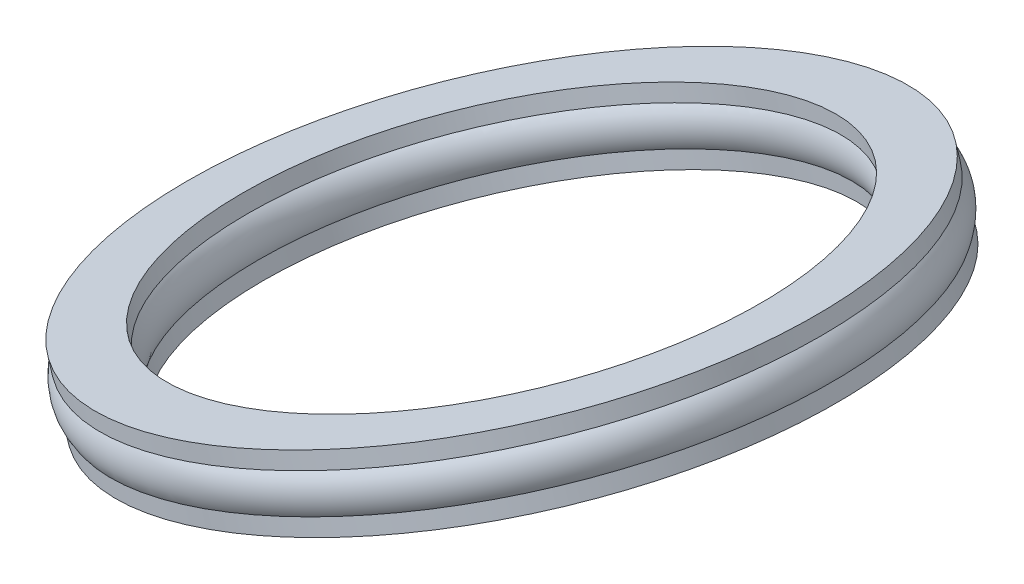
SolidWorks part; units mm, degrees
material "Acero inoxidable al cromo"
ref_plane "Alzado" through (0, 0, 0) normal (0, 0, 1) x (1, 0, 0)
ref_plane "Planta" through (0, 0, 0) normal (0, 1, 0) x (1, 0, 0)
ref_plane "Vista lateral" through (0, 0, 0) normal (1, 0, 0) x (0, 0, -1)
sketch "Sk_Jaula" plane through (0, 0, 0) normal (0, 0, 1) x (1, 0, 0)
  line L0 (380.2637, 538.3273) -> (383.5063, 539.3497)
  line L1 (383.5063, 539.3497) -> (384.7092, 535.5349)
  line L2 (384.7092, 535.5349) -> (381.4665, 534.5124)
  line L3 (381.4665, 534.5124) -> (380.2637, 538.3273)
  line L4 (363.6914, 538.3446) -> (374.2164, 504.9646) construction
revolve "Jaula" add sketch "Sk_Jaula" angle 360 about L4
sketch "Sk_Bolas" plane through (0, 0, 0) normal (0, 0, 1) x (1, 0, 0)
  line L0 (362.7893, 541.2057) -> (368.8036, 522.1314) construction
  circle A0 centre (382.4864, 536.9311) radius 2
  dimension "DIAM1" = 4
revolve "Bolas" add sketch "Sk_Bolas" angle 360 about L0
